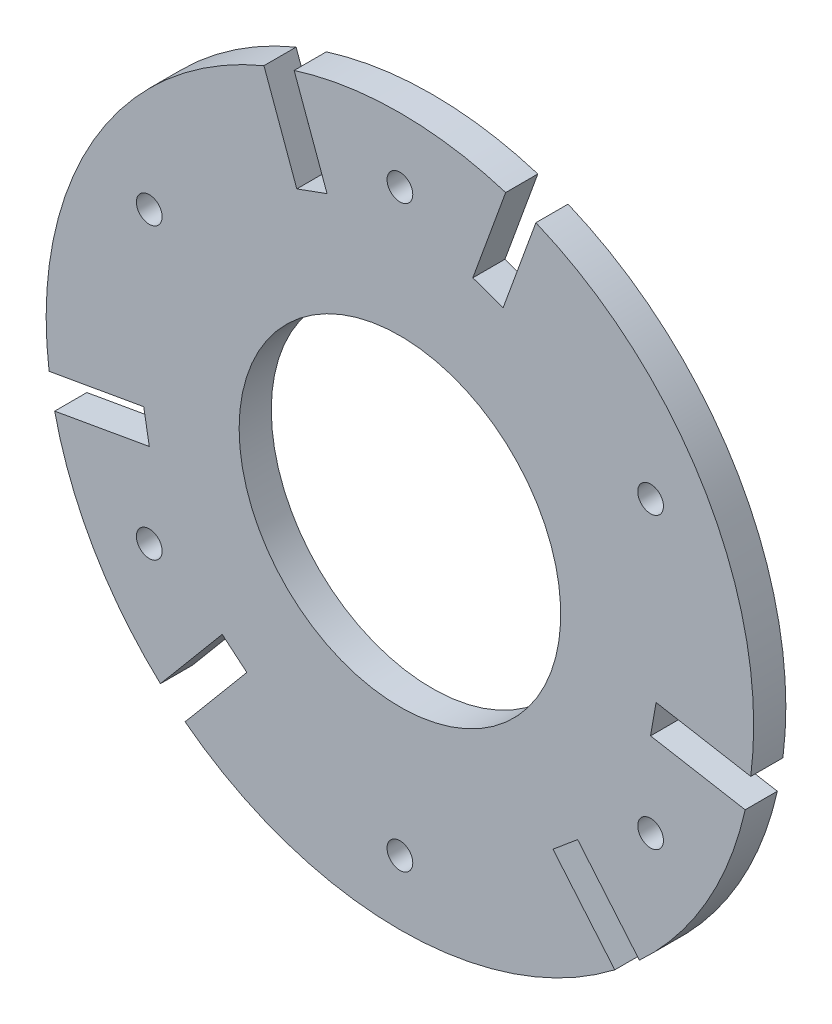
SolidWorks part; units mm, degrees
ref_plane "Alzado" through (0, 0, 0) normal (0, 0, 1) x (1, 0, 0)
ref_plane "Planta" through (0, 0, 0) normal (0, 1, 0) x (1, 0, 0)
ref_plane "Vista lateral" through (0, 0, 0) normal (1, 0, 0) x (0, 0, -1)
sketch "Croquis1" plane through (0, 0, 0) normal (0, 0, 1) x (1, 0, 0)
  circle A0 centre (0, 0) radius 55
  dimension "D1" = 110
extrude "Saliente-Extruir1" add sketch "Croquis1" along normal blind 5
sketch "Croquis2" plane through (0, 0, 5) normal (0, 0, 1) x (1, 0, 0)
  line L0 (0, 62.3189) -> (0, 0) construction
  line L1 (0, 62.3189) -> (0, 0) construction
  line L2 (0, 62.3189) -> (0, 0) construction
  line L3 (0, 0) -> (-22.0381, 60.5491) construction
  line L4 (0, 0) -> (22.0381, 60.5491) construction
  line L5 (-21.1616, 50.8315) -> (-16.0313, 36.7361)
  line L6 (-16.0313, 36.7361) -> (-11.3328, 38.4462)
  line L7 (-11.3328, 38.4462) -> (-16.4631, 52.5416)
  line L8 (-16.4631, 52.5416) -> (-21.1616, 50.8315)
  line L9 (0, 0) -> (63.4561, -11.189) construction
  line L10 (0, 0) -> (41.418, -49.3601) construction
  line L11 (0, 0) -> (-41.418, -49.3601) construction
  line L12 (0, 0) -> (-63.4561, -11.189) construction
  line L13 (16.0313, 36.7361) -> (11.3328, 38.4462)
  line L14 (11.3328, 38.4462) -> (16.4631, 52.5416)
  line L15 (16.4631, 52.5416) -> (21.1616, 50.8315)
  line L16 (21.1616, 50.8315) -> (16.0313, 36.7361)
  line L17 (54.6022, -7.0893) -> (39.8301, -4.4845)
  line L18 (53.7339, -12.0133) -> (54.6022, -7.0893)
  line L19 (38.9618, -9.4086) -> (53.7339, -12.0133)
  line L20 (39.8301, -4.4845) -> (38.9618, -9.4086)
  line L21 (27.629, -29.0376) -> (37.2708, -40.5283)
  line L22 (37.2708, -40.5283) -> (33.4406, -43.7422)
  line L23 (33.4406, -43.7422) -> (23.7988, -32.2516)
  line L24 (23.7988, -32.2516) -> (27.629, -29.0376)
  line L25 (-33.4406, -43.7422) -> (-23.7988, -32.2516)
  line L26 (-37.2708, -40.5283) -> (-33.4406, -43.7422)
  line L27 (-27.629, -29.0376) -> (-37.2708, -40.5283)
  line L28 (-23.7988, -32.2516) -> (-27.629, -29.0376)
  line L29 (-38.9618, -9.4086) -> (-53.7339, -12.0133)
  line L30 (-53.7339, -12.0133) -> (-54.6022, -7.0893)
  line L31 (-54.6022, -7.0893) -> (-39.8301, -4.4845)
  line L32 (-39.8301, -4.4845) -> (-38.9618, -9.4086)
  circle A0 centre (0, 0) radius 10.063 construction
  circle A1 centre (0, 0) radius 55 construction
  point P11 (-3.2913, 0)
  point P15 (-16.2472, 44.6389)
  point P23 (0, 0)
  point P31 (0, 0)
  point P53 (0, 0)
  dimension "D2" = 20
  dimension "D6" = 5
  dimension "D7" = 2.5
  dimension "D8" = 15
  dimension "D9" = 7.5
  dimension "D1" = 3
  dimension "D4" = 3
  dimension "D11" = 3
extrude "Cortar-Extruir1" cut sketch "Croquis2" against normal through all
sketch "Croquis3" plane through (0, 0, 5) normal (0, 0, 1) x (1, 0, 0)
  line L0 (0, 62.3189) -> (0, 0) construction
  line L2 (0, 45) -> (0, 0) construction
  line L4 (0, 0) -> (-38.9711, -22.5) construction
  line L5 (0, 0) -> (38.9711, -22.5) construction
  line L6 (0, 0) -> (0, -45) construction
  circle A0 centre (0, 45) radius 2
  circle A1 centre (0, -45) radius 2
  circle A2 centre (38.9711, -22.5) radius 2
  circle A3 centre (-38.9711, 22.5) radius 2
  circle A4 centre (-38.9711, -22.5) radius 2
  circle A5 centre (38.9711, 22.5) radius 2
  circle A15 centre (-38.9711, 22.5) radius 2 [skipped]
  circle A16 centre (38.9711, 22.5) radius 2 [skipped]
  circle A17 centre (0, -45) radius 2 [skipped]
  point P17 (0, 0)
  point P46 (-0.6263, -0.3058)
  dimension "D4" = 45
  dimension "D5" = 3
  dimension "D6" = 4
  dimension "D2" = 45
  dimension "D9" = 45
  dimension "D10" = 45
  dimension "D3" = 6
extrude "Cortar-Extruir2" cut sketch "Croquis3" against normal blind 10
sketch "Croquis4" plane through (0, 0, 0) normal (0, 0, -1) x (-1, 0, 0)
  circle A0 centre (0, 0) radius 25
  dimension "D1" = 50
extrude "Cortar-Extruir3" cut sketch "Croquis4" against normal through all
